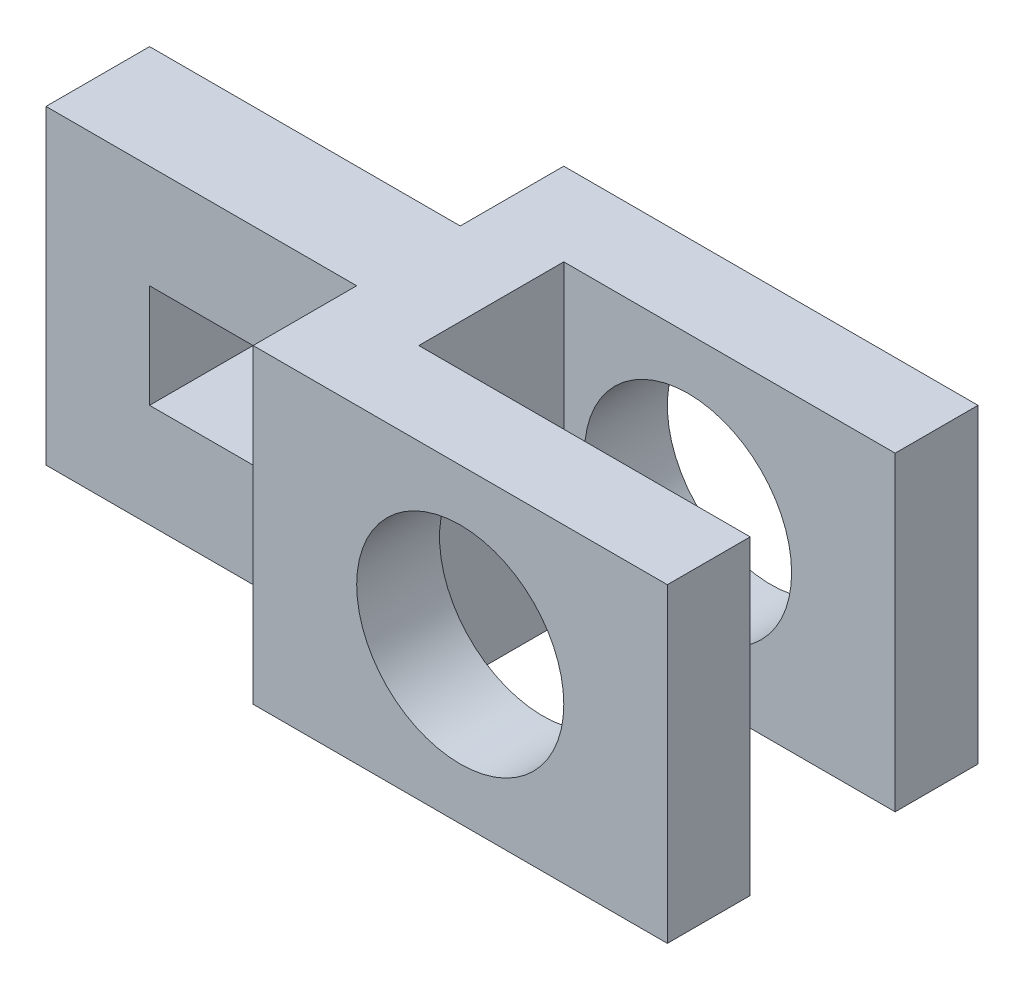
SolidWorks part; units mm, degrees
ref_plane "정면" through (0, 0, 0) normal (0, 0, 1) x (1, 0, 0)
ref_plane "윗면" through (0, 0, 0) normal (0, 1, 0) x (1, 0, 0)
ref_plane "우측면" through (0, 0, 0) normal (1, 0, 0) x (0, 0, -1)
sketch "스케치1" plane through (0, 0, 0) normal (0, 1, 0) x (1, 0, 0)
  line L0 (-30.4963, 3.8677) -> (-30.4963, 13.8661)
  line L1 (-30.4963, 13.8661) -> (-60.4963, 13.8661)
  line L2 (-60.4963, 13.8661) -> (-60.4963, 23.8677)
  line L3 (-30.4963, 3.8677) -> (9.5037, 3.8677)
  line L4 (9.5037, 3.8677) -> (9.5037, 11.8677)
  line L5 (9.5037, 11.8677) -> (-22.4963, 11.8677)
  line L6 (-22.4963, 11.8677) -> (-22.4963, 25.8677)
  line L7 (-22.4963, 25.8677) -> (9.5037, 25.8677)
  line L8 (9.5037, 25.8677) -> (9.5037, 33.8677)
  line L9 (9.5037, 33.8677) -> (-30.4963, 33.8677)
  line L10 (-30.4963, 33.8677) -> (-30.4963, 23.8677)
  line L11 (-60.4963, 23.8677) -> (-30.4963, 23.8677)
  dimension "D1" = 8
extrude "보스-돌출1" add sketch "스케치1" along normal blind 30
sketch "스케치2" plane through (0, 0, -3.8677) normal (0, 0, 1) x (1, 0, 0)
  circle A0 centre (-10.4963, 15) radius 10
extrude "컷-돌출1" cut sketch "스케치2" against normal through all both and the other way through all
sketch "스케치4" plane through (0, 0, -13.8661) normal (0, 0, 1) x (1, 0, 0)
  line L0 (-60.4963, 30) -> (-60.4963, 0) construction
  line L1 (-40.4963, 20) -> (-50.4963, 20)
  line L2 (-40.4963, 20) -> (-40.4963, 10)
  line L3 (-40.4963, 10) -> (-50.4963, 10)
  line L4 (-50.4963, 20) -> (-50.4963, 10)
  line L5 (-60.4963, 30) -> (-30.4963, 30) construction
  dimension "D1" = 10
  dimension "D2" = 10
extrude "컷-돌출2" cut sketch "스케치4" against normal through all
